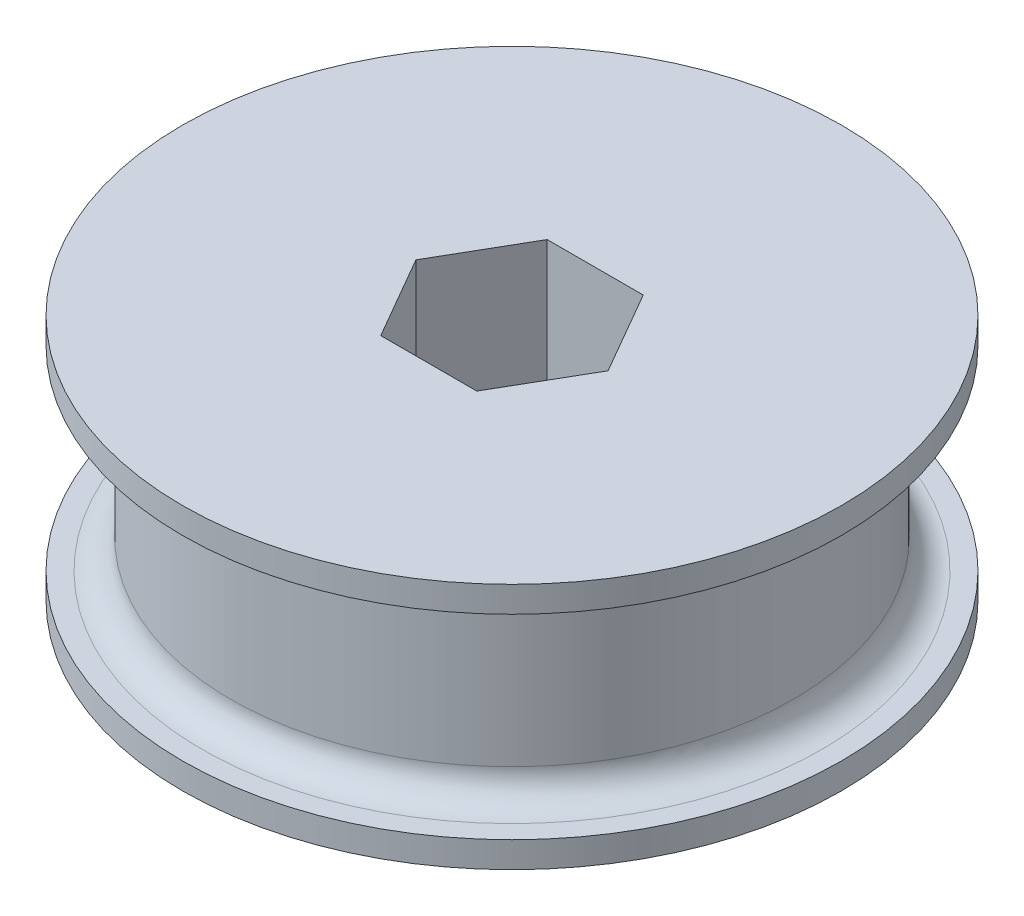
SolidWorks part; units mm, degrees
ref_plane "Front Plane" through (0, 0, 0) normal (0, 0, 1) x (1, 0, 0)
ref_plane "Top Plane" through (0, 0, 0) normal (0, 1, 0) x (1, 0, 0)
ref_plane "Right Plane" through (0, 0, 0) normal (1, 0, 0) x (0, 0, -1)
sketch "Sketch1" plane through (0, 0, 0) normal (0, 1, 0) x (1, 0, 0)
  line L1 (-7.479, 0) -> (-3.7395, -6.477) construction
  line L2 (-3.7395, -6.477) -> (3.7395, -6.477) construction
  line L3 (3.7395, -6.477) -> (7.479, 0) construction
  line L4 (7.479, 0) -> (3.7395, 6.477) construction
  line L5 (3.7395, 6.477) -> (-3.7395, 6.477) construction
  line L6 (-3.7395, 6.477) -> (-7.479, 0) construction
  circle A0 centre (0, 0) radius 6.477 construction
  circle A1 centre (0, 0) radius 25.4
  circle A2 centre (0, 0) radius 4.8387
  dimension "pulley_dia" = 50.8
  dimension "D3" = 9.6774
extrude "Boss-Extrude1" add sketch "Sketch1" along normal blind 19.05
sketch "Sketch6" plane through (0, 19.05, 0) normal (0, 1, 0) x (1, 0, 0)
  line L1 (3.7028, -6.4135) -> (7.4057, 0)
  line L2 (7.4057, 0) -> (3.7028, 6.4135)
  line L3 (3.7028, 6.4135) -> (-3.7028, 6.4135)
  line L4 (-3.7028, 6.4135) -> (-7.4057, 0)
  line L5 (-7.4057, 0) -> (-3.7028, -6.4135)
  line L6 (-3.7028, -6.4135) -> (3.7028, -6.4135)
  circle A0 centre (0, 0) radius 6.4135 construction
  dimension "D1" = 12.827
extrude "Cut-Extrude1" cut sketch "Sketch6" against normal through all
sketch "Sketch2" plane through (0, 0, 0) normal (0, 0, 1) x (1, 0, 0)
  line L0 (0, 0) -> (0, 19.05) construction
  line L1 (25.4, 19.05) -> (-25.4, 19.05) construction
  line L2 (25.4, 0) -> (25.4, 19.05) construction
  line L3 (25.4, 17.0498) -> (23.876, 17.0498)
  line L4 (25.4, 17.0498) -> (25.4, 2.0002)
  line L5 (25.4, 2.0002) -> (23.876, 2.0002)
  line L6 (21.6535, 14.8273) -> (21.6535, 4.2227)
  line L7 (0, 9.525) -> (21.6535, 9.525) construction
  arc A0 (23.876, 2.0002) -> (21.6535, 4.2227) centre (23.876, 4.2227) cw
  arc A1 (21.6535, 14.8273) -> (23.876, 17.0498) centre (23.876, 14.8273) cw
  point P17 (21.6535, 17.0498)
  dimension "cut_radius" = 2.2225
  dimension "cut_thickness" = 15.0495
  dimension "cut_depth" = 3.7465
revolve "Cut-Revolve1" cut sketch "Sketch2" angle 360 about L0
hole_wizard "CBORE for #8 Binding Head Machine Screw1" [suppressed] positions "Sketch4" profile "Sketch5" counterbore size "#8" standard "ANSI Inch"
sketch "Sketch4" plane through (0, 25.4, 0) normal (0, 1, 0) x (1, 0, 0)
  line L0 (0, 0) -> (0, 18.415) construction
  point P0 (0, 18.415)
  dimension "bolt_cir_dia" = 18.415
sketch "Sketch5" plane through (0, 25.4, -18.415) normal (1, 0, 0) x (0, 0, 1)
  line L0 (0, 0) -> (0, 25.4)
  line L1 (0, 25.4) -> (2.2479, 25.4)
  line L3 (2.2479, 25.4) -> (2.2479, 2.667)
  line L4 (2.2479, 2.667) -> (4.7625, 2.667)
  line L5 (4.7625, 2.667) -> (4.7625, 0)
  line L7 (4.7625, 0) -> (0, 0)
  line L11 (0, -6.35) -> (0, 107.95) construction
  dimension "Thru Hole Dia." = 4.4958
  dimension "Thru Hole Depth" = 25.4
  dimension "C'Bore Dia." = 9.525
  dimension "C'Bore Depth" = 2.667
pattern_circular "CirPattern1" [suppressed] count 6 over 360
